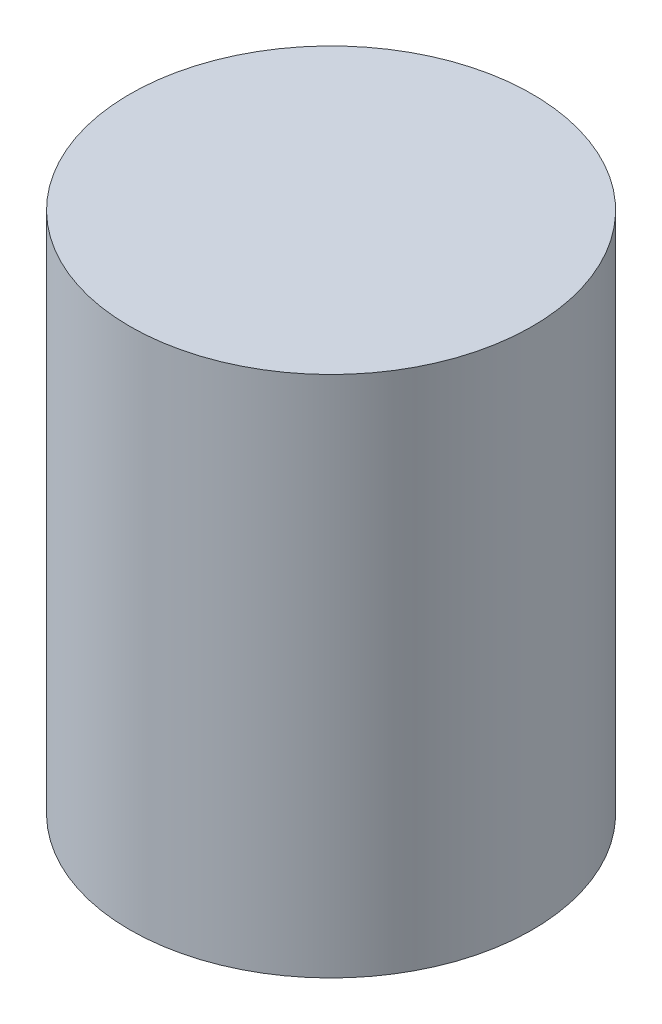
SolidWorks part; units mm, degrees
ref_plane "Front Plane" through (0, 0, 0) normal (0, 0, 1) x (1, 0, 0)
ref_plane "Top Plane" through (0, 0, 0) normal (0, 1, 0) x (1, 0, 0)
ref_plane "Right Plane" through (0, 0, 0) normal (1, 0, 0) x (0, 0, -1)
sketch "Sketch1" plane through (0, 0, 0) normal (0, 1, 0) x (1, 0, 0)
  circle A0 centre (0, 0) radius 3.85
  dimension "D1" = 7.7
extrude "Boss-Extrude1" add sketch "Sketch1" along normal blind 10
